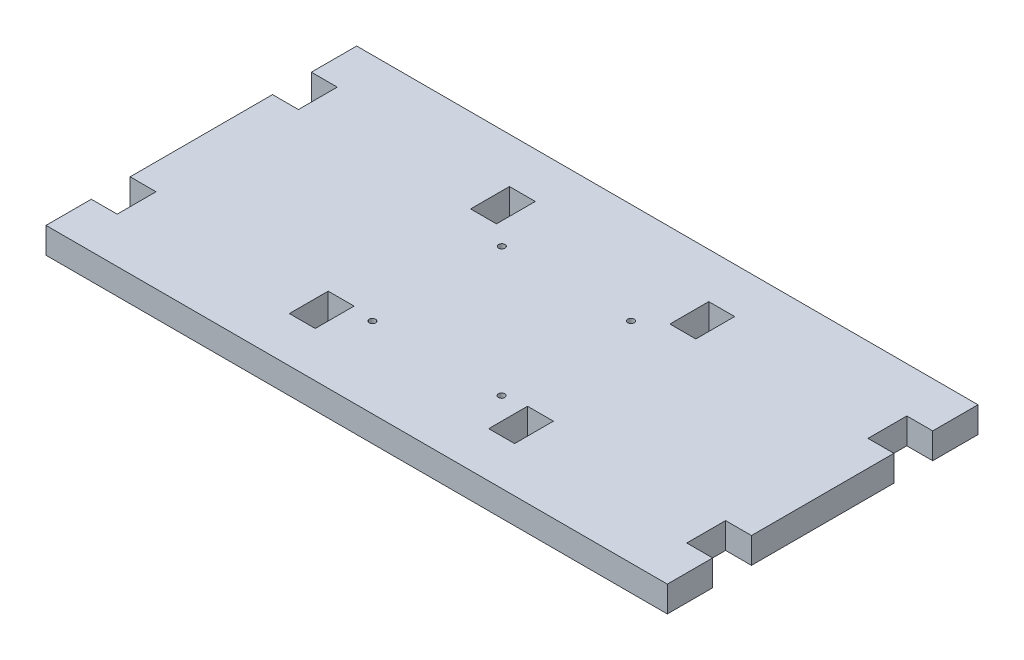
SolidWorks part; units mm, degrees
material "Acrylic (Medium-high impact)"
ref_plane "Front Plane" through (0, 0, 0) normal (0, 0, 1) x (1, 0, 0)
ref_plane "Top Plane" through (0, 0, 0) normal (0, 1, 0) x (1, 0, 0)
ref_plane "Right Plane" through (0, 0, 0) normal (1, 0, 0) x (0, 0, -1)
sketch "Sketch1" plane through (0, 0, 0) normal (0, 1, 0) x (1, 0, 0)
  line L1 (-152.4, 76.2) -> (152.4, 76.2)
  line L2 (-152.4, 76.2) -> (-152.4, -76.2)
  line L3 (-152.4, -76.2) -> (152.4, -76.2)
  line L4 (152.4, 76.2) -> (152.4, -76.2)
  line L5 (-152.4, 76.2) -> (152.4, -76.2) construction
  line L6 (-152.4, -76.2) -> (152.4, 76.2) construction
  point P0 (0, 0)
  dimension "D1" = 152.4
  dimension "D2" = 304.8
extrude "Extrude1" add sketch "Sketch1" along normal blind 12.7
sketch "Sketch2" plane through (0, 12.7, 0) normal (0, 1, 0) x (1, 0, 0)
  line L0 (0, 0) -> (0, 93.8784) construction
  line L1 (0, 0) -> (156.2405, 0) construction
  line L2 (-55.245, 53.975) -> (-55.245, 34.925)
  line L3 (42.545, 53.975) -> (55.245, 53.975)
  line L4 (42.545, 53.975) -> (42.545, 34.925)
  line L5 (42.545, 34.925) -> (55.245, 34.925)
  line L6 (55.245, 53.975) -> (55.245, 34.925)
  line L7 (-42.545, 34.925) -> (-55.245, 34.925)
  line L8 (-42.545, 53.975) -> (-42.545, 34.925)
  line L9 (-42.545, 53.975) -> (-55.245, 53.975)
  line L10 (-42.545, -53.975) -> (-55.245, -53.975)
  line L11 (-42.545, -53.975) -> (-42.545, -34.925)
  line L12 (-42.545, -34.925) -> (-55.245, -34.925)
  line L13 (55.245, -53.975) -> (55.245, -34.925)
  line L14 (42.545, -34.925) -> (55.245, -34.925)
  line L15 (42.545, -53.975) -> (42.545, -34.925)
  line L16 (42.545, -53.975) -> (55.245, -53.975)
  line L17 (-55.245, -53.975) -> (-55.245, -34.925)
  line L18 (152.4, -76.2) -> (152.4, 76.2) construction
  line L19 (152.4, 53.975) -> (139.7, 53.975)
  line L20 (152.4, 53.975) -> (152.4, 34.925)
  line L21 (152.4, 34.925) -> (139.7, 34.925)
  line L22 (139.7, 53.975) -> (139.7, 34.925)
  line L23 (-139.7, 53.975) -> (-139.7, 34.925)
  line L24 (-152.4, 34.925) -> (-139.7, 34.925)
  line L25 (-152.4, 53.975) -> (-152.4, 34.925)
  line L26 (-152.4, 53.975) -> (-139.7, 53.975)
  line L27 (139.7, -53.975) -> (139.7, -34.925)
  line L28 (152.4, -34.925) -> (139.7, -34.925)
  line L29 (152.4, -53.975) -> (152.4, -34.925)
  line L30 (152.4, -53.975) -> (139.7, -53.975)
  line L31 (-152.4, -53.975) -> (-139.7, -53.975)
  line L32 (-152.4, -53.975) -> (-152.4, -34.925)
  line L33 (-152.4, -34.925) -> (-139.7, -34.925)
  line L34 (-139.7, -53.975) -> (-139.7, -34.925)
  dimension "D1" = 19.05
  dimension "D2" = 12.7
  dimension "D3" = 42.545
  dimension "D4" = 34.925
extrude "Extrude2" cut sketch "Sketch2" against normal through all
sketch "Sketch3" plane through (0, 0, 0) normal (0, -1, 0) x (1, 0, 0)
  line L0 (34.8615, 43.1462) -> (34.8615, 30.4462) construction
  line L1 (34.8615, -20.3538) -> (34.8615, -33.0538) construction
  line L2 (0, 0) -> (0, 49.2523) construction
  circle A0 centre (31.6865, 36.7962) radius 1.5875
  circle A1 centre (31.6865, -26.7038) radius 1.5875
  circle A3 centre (-31.6865, -26.7038) radius 1.5875
  circle A4 centre (-31.6865, 36.7962) radius 1.5875
  point P6 (34.8615, 36.7962)
  point P9 (34.8615, -26.7038)
  point P13 (31.6865, 43.1462)
  point P19 (-31.6865, 43.1462)
  dimension "D1" = 3.175
extrude "Cut-Extrude1" cut sketch "Sketch3" against normal through all
